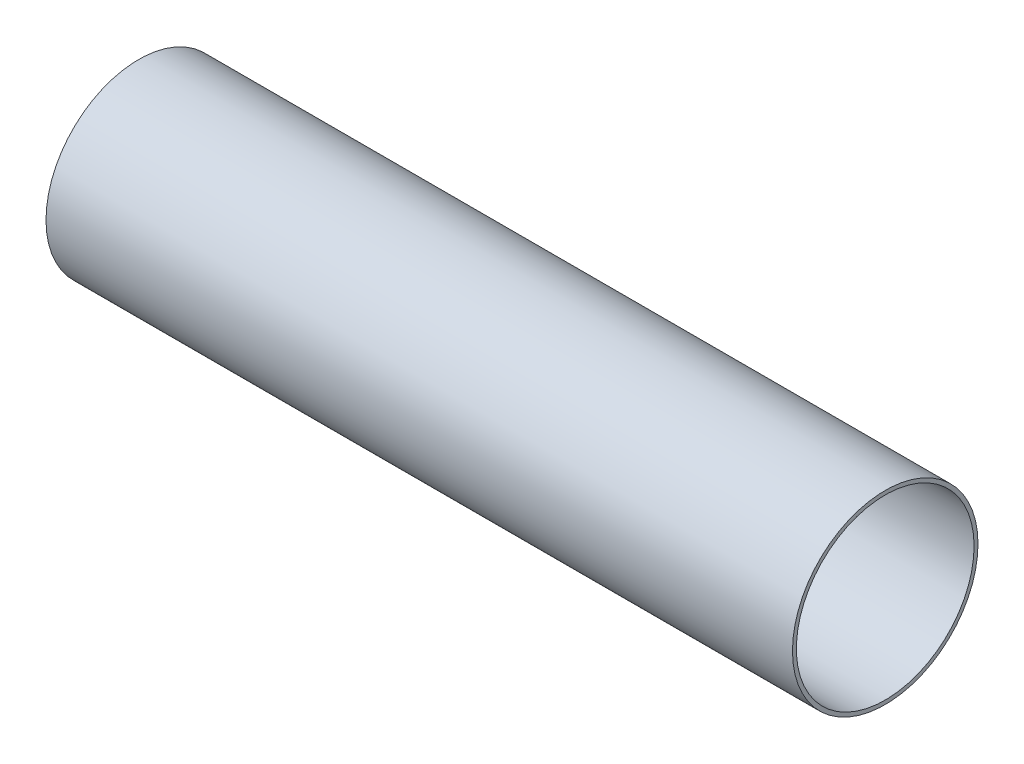
SolidWorks part; units mm, degrees
material "Silicon Rubber"
ref_plane "Front Plane" through (0, 0, 0) normal (0, 0, 1) x (1, 0, 0)
ref_plane "Top Plane" through (0, 0, 0) normal (0, 1, 0) x (1, 0, 0)
ref_plane "Right Plane" through (0, 0, 0) normal (1, 0, 0) x (0, 0, -1)
sketch "Sketch1" plane through (0, 0, 0) normal (1, 0, 0) x (0, 0, -1)
  circle A0 centre (0, 0) radius 25.4
  circle A1 centre (0, 0) radius 26.5165
  dimension "D1" = 53.033
  dimension "D2" = 50.8
extrude "Boss-Extrude1" add sketch "Sketch1" along normal mid plane 213.36
equation "\"D1@Sketch1\"=sqr(1.5^2-1.375^2+4)"
